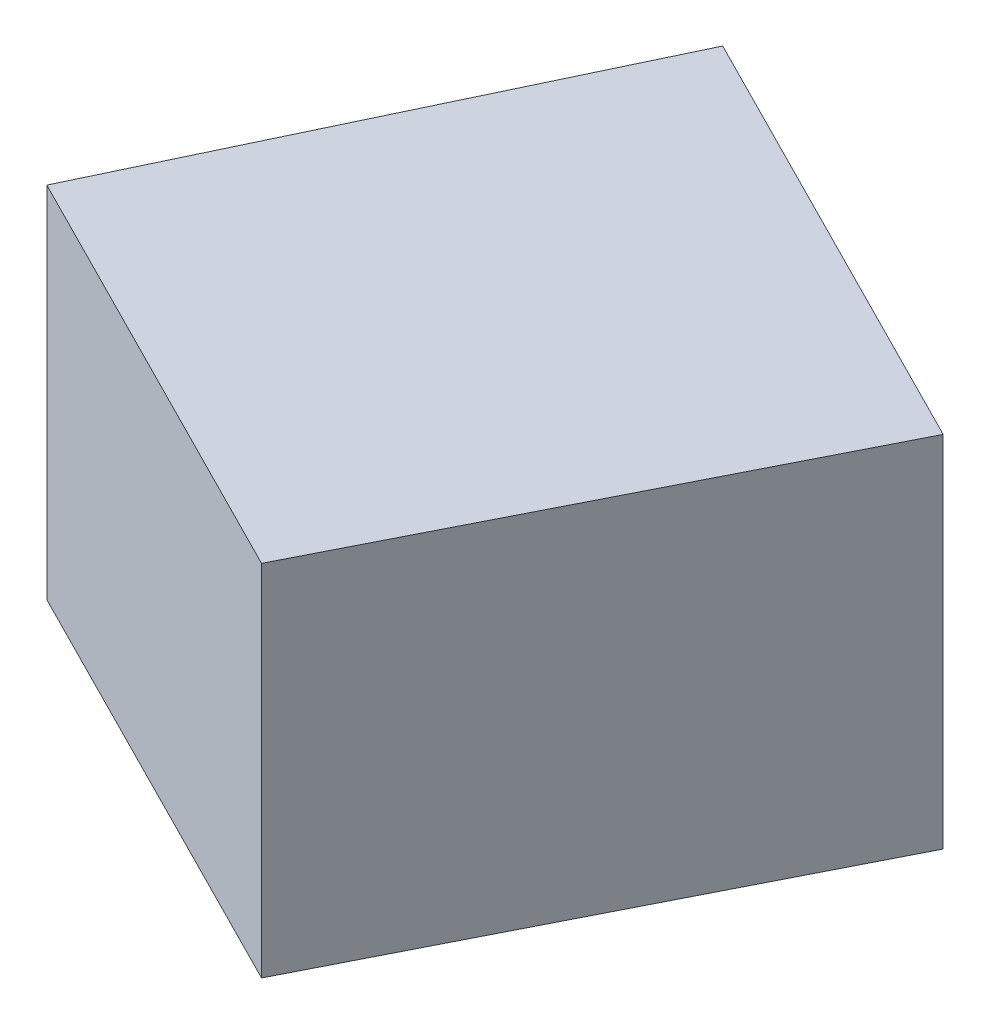
SolidWorks part; units mm, degrees
ref_plane "Front Plane" through (0, 0, 0) normal (0, 0, 1) x (1, 0, 0)
ref_plane "Top Plane" through (0, 0, 0) normal (0, 1, 0) x (1, 0, 0)
ref_plane "Right Plane" through (0, 0, 0) normal (1, 0, 0) x (0, 0, -1)
sketch "Sketch1" plane through (0, 0, 0) normal (0, 1, 0) x (1, 0, 0)
  line L0 (-61.0566, -7.2804) -> (7.9871, -42.2393)
  line L1 (7.9871, -42.2393) -> (44.357, 29.5913)
  line L2 (44.357, 29.5913) -> (-26.5348, 65.4859)
  line L3 (-26.5348, 65.4859) -> (-61.0566, -7.2804)
extrude "Boss-Extrude1" add sketch "Sketch1" along normal blind 57
